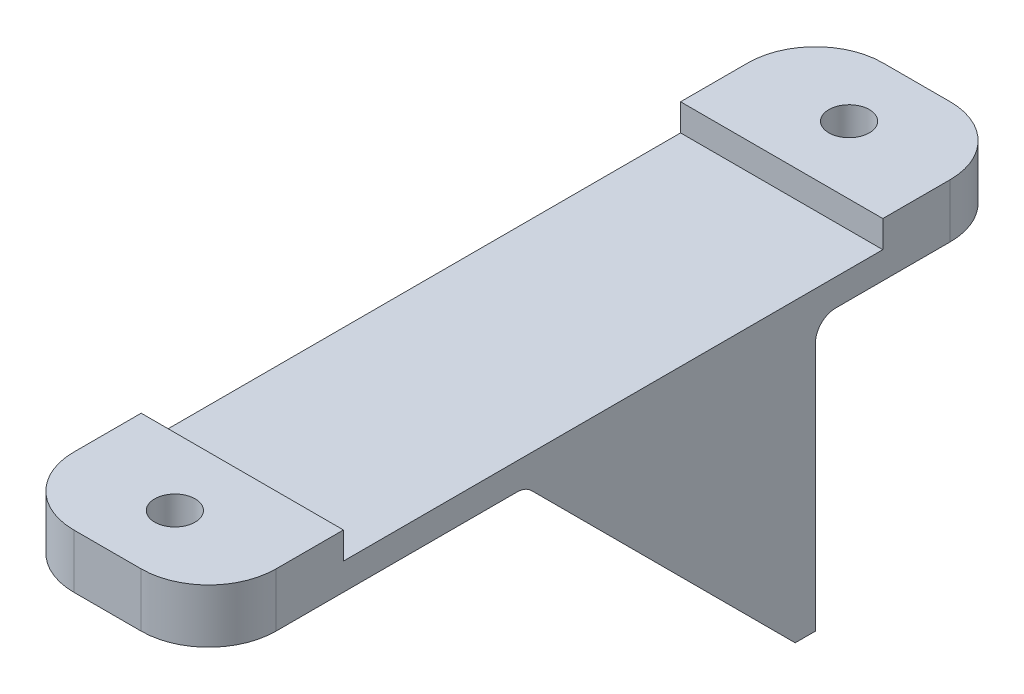
SolidWorks part; units mm, degrees
ref_plane "Front Plane" through (0, 0, 0) normal (0, 0, 1) x (1, 0, 0)
ref_plane "Top Plane" through (0, 0, 0) normal (0, 1, 0) x (1, 0, 0)
ref_plane "Right Plane" through (0, 0, 0) normal (1, 0, 0) x (0, 0, -1)
sketch "Sketch1" plane through (0, 0, 0) normal (0, 1, 0) x (1, 0, 0)
  line L1 (0, 0) -> (30, 0)
  line L2 (0, 0) -> (0, 120)
  line L3 (0, 120) -> (30, 120)
  line L4 (30, 0) -> (30, 120)
  dimension "D1" = 120
  dimension "D2" = 30
extrude "Boss-Extrude1" add sketch "Sketch1" along normal blind 8
sketch "Sketch2" plane through (0, 8, 0) normal (0, 1, 0) x (1, 0, 0)
  line L0 (0, 120) -> (0, 0) construction
  line L1 (30, 100) -> (0, 100)
  line L2 (30, 100) -> (30, 20)
  line L3 (30, 20) -> (0, 20)
  line L4 (0, 100) -> (0, 20)
  line L5 (30, 100) -> (0, 20) construction
  line L6 (30, 20) -> (0, 100) construction
  line L7 (30, 120) -> (0, 120) construction
  point P0 (15, 60)
  dimension "D1" = 80
  dimension "D2" = 30
  dimension "D3" = 20
extrude "Cut-Extrude1" cut sketch "Sketch2" against normal blind 4
sketch "Sketch3" plane through (0, 0, 0) normal (0, -1, 0) x (1, 0, 0)
  line L0 (0, -120) -> (0, 0) construction
  line L1 (0, -87) -> (30, -87)
  line L2 (0, -87) -> (0, -90)
  line L3 (0, -90) -> (30, -90)
  line L4 (30, -87) -> (30, -90)
  line L5 (30, 0) -> (30, -120) construction
  line L7 (30, -120) -> (0, -120) construction
  dimension "D1" = 30
  dimension "D2" = 3
extrude "Boss-Extrude2" add sketch "Sketch3" along normal blind 40
sketch "Sketch4" plane through (0, 0, -87) normal (0, 0, 1) x (1, 0, 0)
  line L0 (30, -40) -> (0, -40) construction
  line L1 (0, -40) -> (0, 0) construction
  circle A0 centre (15, -20) radius 9.1
  dimension "D2" = 18.2
  dimension "D3" = 15
  dimension "D1" = 20
extrude "Cut-Extrude2" cut sketch "Sketch4" against normal blind 40
sketch "Sketch5" plane through (30, 0, 0) normal (1, 0, 0) x (0, 0, -1)
  line L0 (87, -40) -> (47, 0)
  line L1 (0, 0) -> (87, 0) construction
  line L3 (87, 0) -> (87, -40)
  line L4 (47, 0) -> (87, 0)
  dimension "D1" = 45
extrude "Boss-Extrude3" add sketch "Sketch5" against normal blind 2.5
sketch "Sketch6" plane through (0, 0, 0) normal (-1, 0, 0) x (0, 0, 1)
  line L0 (-47, 0) -> (-87, -40) construction
  line L1 (-87, 0) -> (0, 0) construction
  line L2 (-87, -40) -> (-87, 0) construction
  line L3 (-47, 0) -> (-87, -40)
  line L4 (-87, 0) -> (-47, 0)
  line L5 (-87, -40) -> (-87, 0)
extrude "Boss-Extrude4" add sketch "Sketch6" against normal blind 2.5
sketch "Sketch7" plane through (0, 0, 0) normal (0, -1, 0) x (-1, 0, 0)
  line L0 (-30, 0) -> (-30, 47) construction
  line L1 (0, 0) -> (-30, 0) construction
  line L2 (-30, 120) -> (0, 120) construction
  line L3 (0, 120) -> (0, 90) construction
  circle A0 centre (-15, 10) radius 3
  circle A1 centre (-15, 110) radius 3
  dimension "D3" = 6
  dimension "D4" = 6
  dimension "D5" = 10
  dimension "D6" = 15
  dimension "D1" = 15
  dimension "D2" = 10
extrude "Cut-Extrude3" cut sketch "Sketch7" against normal through all
fillet "Fillet1" radius 10 4 edges at (30, 4, -120) (0, 4, -120) (30, 4, 0) (0, 4, 0)
fillet "Fillet2" radius 3 1 edges at (15, 0, -90)
fillet "Fillet3" radius 3 2 edges at (28.75, 0, -47) (1.25, 0, -47)
